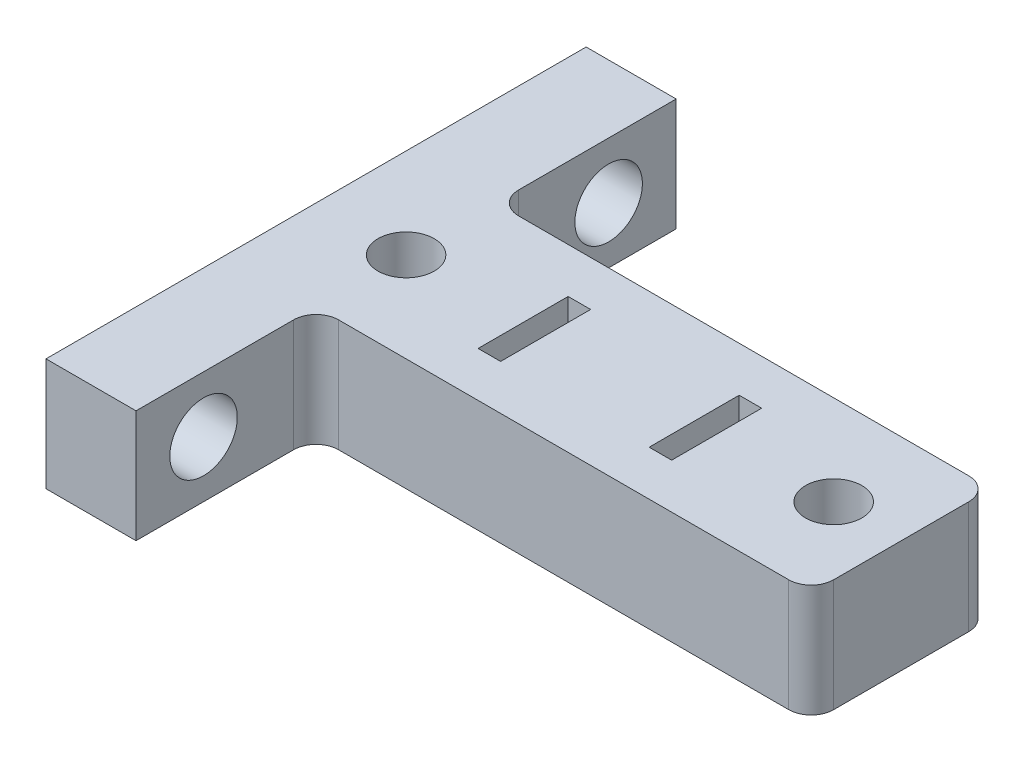
SolidWorks part; units mm, degrees
ref_plane "Front Plane" through (0, 0, 0) normal (0, 0, 1) x (1, 0, 0)
ref_plane "Top Plane" through (0, 0, 0) normal (0, 1, 0) x (1, 0, 0)
ref_plane "Right Plane" through (0, 0, 0) normal (1, 0, 0) x (0, 0, -1)
sketch "Sketch1" plane through (0, 0, 0) normal (0, 1, 0) x (1, 0, 0)
  line L0 (-13, -3) -> (-13, -12)
  line L1 (-8, 4) -> (12, 4)
  line L2 (-13, 4) -> (-13, -3)
  line L3 (-8, -4) -> (12, -4)
  line L4 (13, 3) -> (13, -3)
  line L5 (-13, 4) -> (-13, 12)
  line L6 (-13, -12) -> (-9, -12)
  line L7 (-13, 12) -> (-9, 12)
  line L8 (-9, -12) -> (-9, -5)
  line L9 (-9, 12) -> (-9, 5)
  line L11 (4.8, -2) -> (3.8, -2)
  line L12 (4.8, -2) -> (4.8, 2)
  line L13 (4.8, 2) -> (3.8, 2)
  line L14 (3.8, -2) -> (3.8, 2)
  line L15 (-2.8, -2) -> (-3.8, -2)
  line L16 (-2.8, -2) -> (-2.8, 2)
  line L17 (-2.8, 2) -> (-3.8, 2)
  line L18 (-3.8, -2) -> (-3.8, 2)
  circle A0 centre (10, 0) radius 1.25
  circle A1 centre (-9, 0) radius 1.25
  arc A2 (12, -4) -> (13, -3) centre (12, -3) ccw
  arc A3 (13, 3) -> (12, 4) centre (12, 3) ccw
  arc A4 (-9, 5) -> (-8, 4) centre (-8, 5) ccw
  arc A5 (-9, -5) -> (-8, -4) centre (-8, -5) cw
  point P11 (13, -4)
  point P14 (13, 4)
  dimension "D5" = 2.5
  dimension "D6" = 2.5
  dimension "D11" = 1
  dimension "D16" = 1
  dimension "D1" = 8
  dimension "D2" = 26
  dimension "D3" = 13
  dimension "D4" = 4
  dimension "D7" = 19
  dimension "D8" = 4
  dimension "D9" = 4
  dimension "D10" = 3
  dimension "D12" = 12
  dimension "D13" = 12
  dimension "D14" = 4
  dimension "D15" = 4
  dimension "D17" = 5.2
  dimension "D18" = 5.2
  dimension "D19" = 4
  dimension "D20" = 2
  dimension "D21" = 1
extrude "Boss-Extrude1" add sketch "Sketch1" along normal blind 5
sketch "Sketch3" plane through (-13, 0, 0) normal (-1, 0, 0) x (0, 0, 1)
  line L0 (-12, 5) -> (12, 5) construction
  line L1 (-12, 5) -> (-12, 0) construction
  line L2 (12, 5) -> (12, 0) construction
  circle A0 centre (9, 2.5) radius 1.5
  circle A1 centre (-9, 2.5) radius 1.5
  dimension "D1" = 3
  dimension "D2" = 3
  dimension "D3" = 2.5
  dimension "D4" = 2.5
  dimension "D5" = 3
  dimension "D6" = 3
extrude "Cut-Extrude1" cut sketch "Sketch3" against normal blind 4
